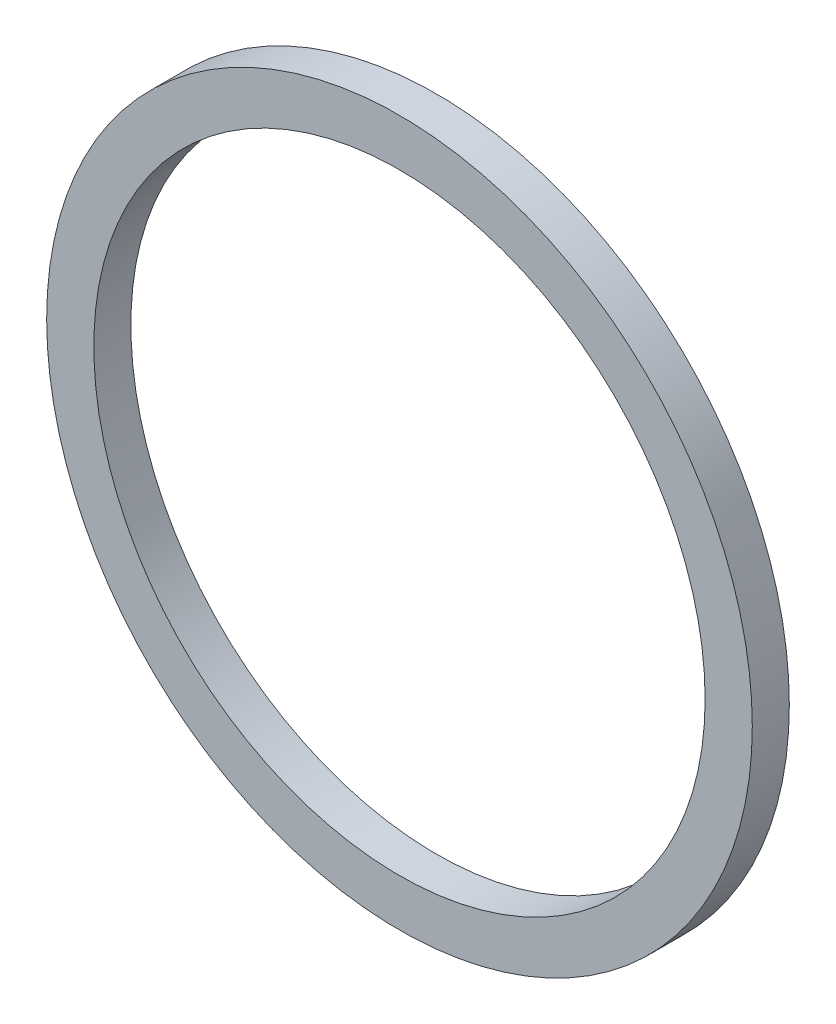
SolidWorks part; units mm, degrees
material "Copper"
ref_plane "Front Plane" through (0, 0, 0) normal (0, 0, 1) x (1, 0, 0)
ref_plane "Top Plane" through (0, 0, 0) normal (0, 1, 0) x (1, 0, 0)
ref_plane "Right Plane" through (0, 0, 0) normal (1, 0, 0) x (0, 0, -1)
sketch "Sketch1" plane through (0, 0, 0) normal (0, 0, 1) x (1, 0, 0)
  circle A0 centre (0, 0) radius 18.15
  circle A1 centre (0, 0) radius 20.95
  dimension "ID" = 36.3
  dimension "OD" = 41.9
extrude "Extrude1" add sketch "Sketch1" against normal blind 2.2
